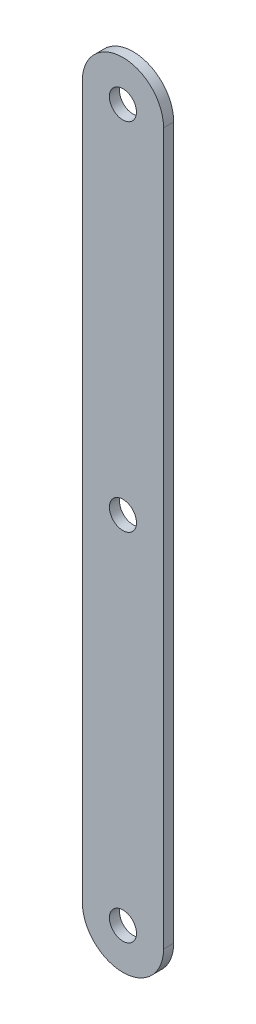
SolidWorks part; units mm, degrees
material "1060 Alloy"
ref_plane "Ön Düzlem" through (0, 0, 0) normal (0, 0, 1) x (1, 0, 0)
ref_plane "Üst Düzlem" through (0, 0, 0) normal (0, 1, 0) x (1, 0, 0)
ref_plane "Sağ Düzlem" through (0, 0, 0) normal (1, 0, 0) x (0, 0, -1)
ref_plane "Düzlem1" through (0, 0, -1.5) normal (0, 0, -1) x (-1, 0, 0)
sketch "Çizim1" plane through (0, 0, -1.5) normal (0, 0, -1) x (-1, 0, 0)
  line L0 (12, -105) -> (12, 105)
  line L1 (-12, 105) -> (-12, -105)
  circle A0 centre (0, -105) radius 4
  arc A1 (-12, -105) -> (12, -105) centre (0, -105) ccw
  arc A2 (12, 105) -> (-12, 105) centre (0, 105) ccw
  circle A3 centre (0, 0) radius 4
  circle A4 centre (0, 105) radius 4
  dimension "D2" = 8
  dimension "D3" = 8
  dimension "D4" = 8
  dimension "D1" = 210
extrude "Yükseklik-Ekstrüzyon1" add sketch "Çizim1" against normal blind 3
